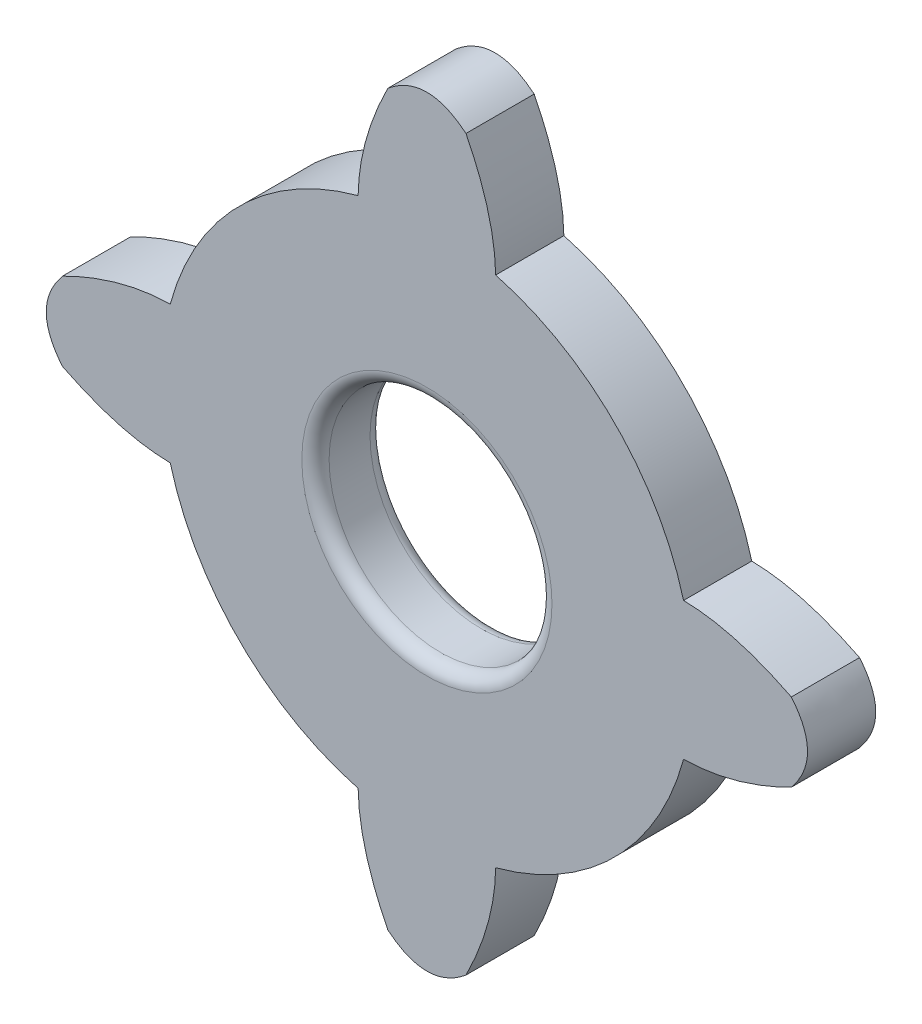
SolidWorks part; units mm, degrees
ref_plane "Front Plane" through (0, 0, 0) normal (0, 0, 1) x (1, 0, 0)
ref_plane "Top Plane" through (0, 0, 0) normal (0, 1, 0) x (1, 0, 0)
ref_plane "Right Plane" through (0, 0, 0) normal (1, 0, 0) x (0, 0, -1)
sketch "Sketch1" plane through (0, 0, 0) normal (0, 0, 1) x (1, 0, 0)
  line L0 (0, 38.9575) -> (0, 62.1414) construction
  line L1 (-5.7304, 53.4351) -> (5.7304, 53.4351) construction
  line L2 (-11.9651, 45.0097) -> (11.9651, 45.0097) construction
  line L3 (-5.7304, 53.4351) -> (0, 58.1785) construction
  line L4 (0, 58.1785) -> (5.7304, 53.4351) construction
  line L5 (-5.7304, 53.4351) -> (-9.977, 45.0097) construction
  line L6 (-9.977, 45.0097) -> (-10.0829, 37.63) construction
  line L7 (5.7304, 53.4351) -> (9.977, 45.0097) construction
  line L8 (9.977, 45.0097) -> (10.0829, 37.63) construction
  line L9 (-10.0829, 37.63) -> (0, 0) construction
  line L10 (0, 0) -> (10.0829, 37.63) construction
  line L11 (53.4351, 5.7304) -> (58.1785, 0) construction
  line L12 (58.1785, 0) -> (53.4351, -5.7304) construction
  line L13 (53.4351, 5.7304) -> (45.0097, 9.977) construction
  line L14 (45.0097, 9.977) -> (37.63, 10.0829) construction
  line L15 (53.4351, -5.7304) -> (45.0097, -9.977) construction
  line L16 (45.0097, -9.977) -> (37.63, -10.0829) construction
  line L17 (5.7304, -53.4351) -> (0, -58.1785) construction
  line L18 (0, -58.1785) -> (-5.7304, -53.4351) construction
  line L19 (5.7304, -53.4351) -> (9.977, -45.0097) construction
  line L20 (9.977, -45.0097) -> (10.0829, -37.63) construction
  line L21 (-5.7304, -53.4351) -> (-9.977, -45.0097) construction
  line L22 (-9.977, -45.0097) -> (-10.0829, -37.63) construction
  line L23 (-53.4351, -5.7304) -> (-58.1785, 0) construction
  line L24 (-58.1785, 0) -> (-53.4351, 5.7304) construction
  line L25 (-53.4351, -5.7304) -> (-45.0097, -9.977) construction
  line L26 (-45.0097, -9.977) -> (-37.63, -10.0829) construction
  line L27 (-53.4351, 5.7304) -> (-45.0097, 9.977) construction
  line L28 (-45.0097, 9.977) -> (-37.63, 10.0829) construction
  arc A0 (-37.63, -10.0829) -> (-10.0829, -37.63) centre (0, 0) ccw
  circle A1 centre (0, 0) radius 16.342
  arc A2 (-10.0829, 37.63) -> (-37.63, 10.0829) centre (0, 0) ccw
  arc A3 (37.63, 10.0829) -> (10.0829, 37.63) centre (0, 0) ccw
  arc A4 (10.0829, -37.63) -> (37.63, -10.0829) centre (0, 0) ccw
  circle A5 centre (0, 0) radius 38.9575 construction
  spline S0 degree 2 poles (-5.7304, 53.4351) (0, 58.1785) (5.7304, 53.4351) knots 0 0 0 1 1 1
  spline S1 degree 2 poles (-5.7304, 53.4351) (-9.977, 45.0097) (-10.0829, 37.63) knots 0 0 0 1 1 1
  spline S2 degree 2 poles (5.7304, 53.4351) (9.977, 45.0097) (10.0829, 37.63) knots 0 0 0 1 1 1
  spline S3 degree 2 poles (53.4351, 5.7304) (45.0097, 9.977) (37.63, 10.0829) knots 0 0 0 1 1 1
  spline S4 degree 2 poles (53.4351, 5.7304) (58.1785, 0) (53.4351, -5.7304) knots 0 0 0 1 1 1
  spline S5 degree 2 poles (53.4351, -5.7304) (45.0097, -9.977) (37.63, -10.0829) knots 0 0 0 1 1 1
  spline S6 degree 2 poles (5.7304, -53.4351) (9.977, -45.0097) (10.0829, -37.63) knots 0 0 0 1 1 1
  spline S7 degree 2 poles (5.7304, -53.4351) (0, -58.1785) (-5.7304, -53.4351) knots 0 0 0 1 1 1
  spline S8 degree 2 poles (-5.7304, -53.4351) (-9.977, -45.0097) (-10.0829, -37.63) knots 0 0 0 1 1 1
  spline S9 degree 2 poles (-53.4351, -5.7304) (-45.0097, -9.977) (-37.63, -10.0829) knots 0 0 0 1 1 1
  spline S10 degree 2 poles (-53.4351, -5.7304) (-58.1785, 0) (-53.4351, 5.7304) knots 0 0 0 1 1 1
  spline S11 degree 2 poles (-53.4351, 5.7304) (-45.0097, 9.977) (-37.63, 10.0829) knots 0 0 0 1 1 1
  point P12 (0, 45.0097)
  point P40 (0, 0)
  dimension "D1" = 30
  dimension "D2" = 4
extrude "Boss-Extrude1" add sketch "Sketch1" along normal blind 10
fillet "Fillet1" radius 2 1 edges at (16.342, 0, 0)
fillet "Fillet2" radius 2 1 edges at (16.342, 0, 10)
